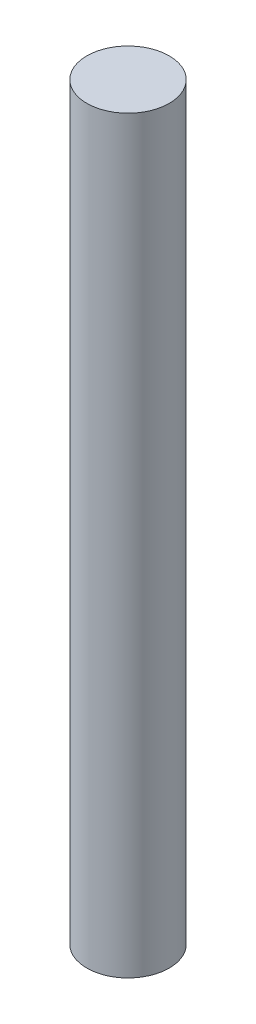
SolidWorks part; units mm, degrees
material "Nylon 101"
ref_plane "Alzado" through (0, 0, 0) normal (0, 0, 1) x (1, 0, 0)
ref_plane "Planta" through (0, 0, 0) normal (0, 1, 0) x (1, 0, 0)
ref_plane "Vista lateral" through (0, 0, 0) normal (1, 0, 0) x (0, 0, -1)
sketch "Sketch1" plane through (0, 0, 0) normal (0, 0, 1) x (1, 0, 0)
  line L0 (0, 0) -> (1.1, 0)
  line L1 (1.1, 0) -> (1.1, -20)
  line L2 (1.1, -20) -> (0, -20)
  line L3 (0, -20) -> (0, 0)
  line L4 (0, -24) -> (0, 4) construction
revolve "Tendon" add sketch "Sketch1" angle 360 about L4
